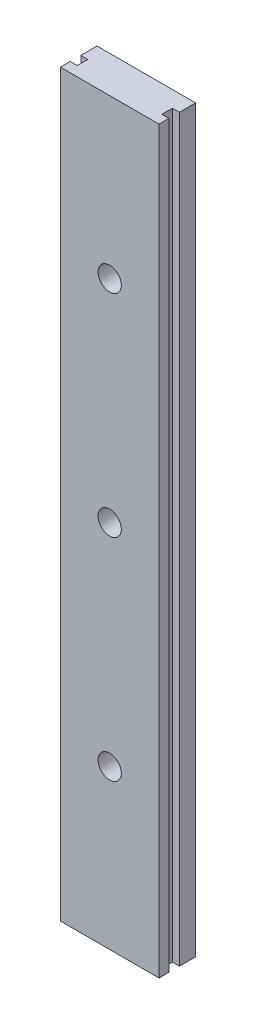
SolidWorks part; units mm, degrees
ref_plane "前视基准面" through (0, 0, 0) normal (0, 0, 1) x (1, 0, 0)
ref_plane "上视基准面" through (0, 0, 0) normal (0, 1, 0) x (1, 0, 0)
ref_plane "右视基准面" through (0, 0, 0) normal (1, 0, 0) x (0, 0, -1)
sketch "草图1" plane through (0, 0, 0) normal (0, 1, 0) x (1, 0, 0)
  line L0 (0, 0) -> (0, 1.4)
  line L1 (0, 1.4) -> (1, 1.4)
  line L2 (1, 1.4) -> (1, 2.9)
  line L3 (1, 2.9) -> (0, 2.9)
  line L4 (0, 2.9) -> (0, 5.2)
  line L5 (0, 5.2) -> (14, 5.2)
  line L6 (0, 0) -> (14, 0)
  line L7 (7, 5.2) -> (7, -2.1169) construction
  line L8 (14, 2.9) -> (14, 5.2)
  line L9 (13, 2.9) -> (14, 2.9)
  line L10 (13, 1.4) -> (13, 2.9)
  line L11 (14, 1.4) -> (13, 1.4)
  line L12 (14, 0) -> (14, 1.4)
  point P11 (7, 0)
  dimension "D1" = 5.2
  dimension "D2" = 14
  dimension "D3" = 1.5
  dimension "D4" = 2.3
  dimension "D5" = 1
extrude "凸台-拉伸1" add sketch "草图1" along normal blind 105
sketch "草图2" plane through (0, 0, -5.2) normal (0, 0, -1) x (-1, 0, 0)
  line L0 (-14, 0) -> (0, 0) construction
  line L1 (-7, 0) -> (-7, 187.5272) construction
  line L2 (-14, 52.5) -> (28.6734, 52.5) construction
  line L3 (-14, 105) -> (-14, 0) construction
  circle A7 centre (-7, 52.5) radius 1.65
  circle A8 centre (-7, 82.5) radius 1.65
  circle A9 centre (-7, 22.5) radius 1.65
  dimension "D1" = 3.3
  dimension "D2" = 30
  dimension "D3" = 30
extrude "切除-拉伸1" cut sketch "草图2" against normal through all
